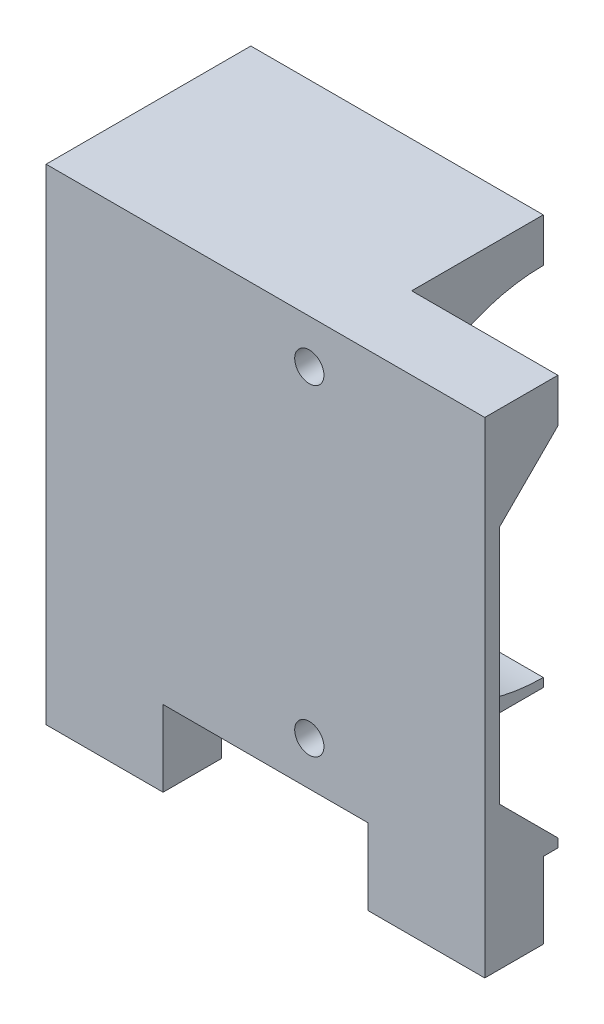
SolidWorks part; units mm, degrees
ref_plane "前视基准面" through (0, 0, 0) normal (0, 0, 1) x (1, 0, 0)
ref_plane "上视基准面" through (0, 0, 0) normal (0, 1, 0) x (1, 0, 0)
ref_plane "右视基准面" through (0, 0, 0) normal (1, 0, 0) x (0, 0, -1)
sketch "草图1" plane through (0, 0, 0) normal (1, 0, 0) x (0, 0, -1)
  line L1 (0, 12.2) -> (-14, 12.2)
  line L3 (0, -12.2) -> (-14, -12.2)
  line L4 (-14, 12.2) -> (-14, -12.2)
  arc A0 (0, 12.2) -> (0, -12.2) centre (0, 0) ccw
  dimension "D1" = 24.4
  dimension "D2" = 14
extrude "凸台-拉伸1" add sketch "草图1" along normal blind 20
sketch "草图2" plane through (20, 0, 0) normal (1, 0, 0) x (0, 0, -1)
  line L0 (-14, -12.2) -> (0, -12.2) construction
  line L1 (-14, 12.2) -> (-13, 12.2)
  line L2 (-14, 12.2) -> (-14, -12.2)
  line L3 (-14, -12.2) -> (-13, -12.2)
  line L4 (-13, 12.2) -> (-13, -12.2)
  dimension "D1" = 1
extrude "凸台-拉伸2" add sketch "草图2" along normal blind 10
sketch "草图6" plane through (0, -12.2, 0) normal (0, -1, 0) x (1, 0, 0)
  line L0 (0, 14) -> (0, 0)
  line L1 (0, 0) -> (20, 0)
  line L2 (20, 0) -> (20, 13)
  line L3 (20, 13) -> (30, 13)
  line L4 (30, 13) -> (30, 14)
  line L5 (30, 14) -> (0, 14)
extrude "凸台-拉伸4" add sketch "草图6" along normal blind 0.6
sketch "草图7" plane through (20, 0, 0) normal (1, 0, 0) x (0, 0, -1)
  line L0 (0, -12.2) -> (-9, -12.2)
  line L1 (-13, -12.8) -> (-13, 12.2) construction
  line L2 (-13, -8.2) -> (-9, -12.2)
  line L3 (-13, 8.2) -> (-9, 12.2)
  line L4 (0, 12.2) -> (-13, 12.2) construction
  line L5 (-9, 12.2) -> (-13, 12.2)
  line L6 (-13, 12.2) -> (-13, 8.2)
  line L7 (-13, -8.2) -> (-13, -12.8)
  line L8 (-13, -12.8) -> (0, -12.8)
  line L9 (0, -12.8) -> (0, -12.2)
  dimension "D1" = 45
  dimension "D3" = 4
  dimension "D4" = 45
extrude "凸台-拉伸5" add sketch "草图7" along normal up to surface (10 mm away) up to face at (30, -0.3, 13.5)
sketch "草图8" plane through (0, -12.8, 0) normal (0, -1, 0) x (1, 0, 0)
  line L0 (30, 0) -> (30, 14) construction
  line L1 (0, 14) -> (8, 14)
  line L2 (0, 14) -> (0, 10)
  line L3 (0, 10) -> (8, 10)
  line L4 (30, 14) -> (30, 10)
  line L5 (22, 10) -> (30, 10)
  line L7 (8, 14) -> (8, 10)
  line L9 (22, 14) -> (22, 10)
  line L10 (22, 14) -> (30, 14)
  dimension "D1" = 4
  dimension "D2" = 14
  dimension "D3" = 8
extrude "凸台-拉伸6" add sketch "草图8" along normal blind 5.2
sketch "草图9" plane through (0, 12.2, 0) normal (0, 1, 0) x (1, 0, 0)
  line L1 (0, 0) -> (20, 0)
  line L2 (0, 0) -> (0, -14)
  line L3 (0, -14) -> (30, -14)
  line L4 (30, -9) -> (30, -14)
  line L5 (20, -9) -> (30, -9)
  line L6 (20, -9) -> (20, 0)
extrude "凸台-拉伸7" add sketch "草图9" along normal blind 3
sketch "草图3" plane through (0, 0, 14) normal (0, 0, 1) x (1, 0, 0)
  line L1 (0, 15.2) -> (0, -18) construction
  line L2 (22, -12.8) -> (8, -12.8) construction
  circle A0 centre (18, 12.2) radius 1
  circle A1 centre (18, -9.8) radius 1
  dimension "D3" = 18
  dimension "D4" = 2
  dimension "D5" = 2
  dimension "D1" = 22
  dimension "D2" = 3
extrude "切除-拉伸1" cut sketch "草图3" against normal through all
sketch "草图10" plane through (0, -12.2, 0) normal (0, 1, 0) x (1, 0, 0)
  line L1 (20, -9) -> (30, -9)
  line L2 (20, -9) -> (20, 0)
  line L3 (20, 0) -> (30, 0)
  line L4 (30, -9) -> (30, 0)
extrude "切除-拉伸2" cut sketch "草图10" against normal blind 3
